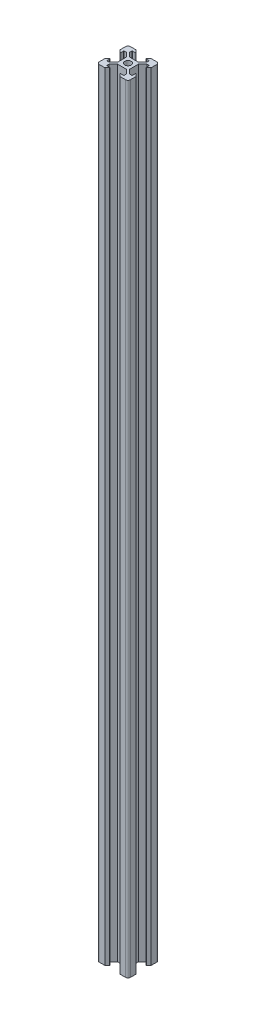
SolidWorks part; units mm, degrees
ref_plane "Alzado" through (0, 0, 0) normal (0, 0, 1) x (1, 0, 0)
ref_plane "Planta" through (0, 0, 0) normal (0, 1, 0) x (1, 0, 0)
ref_plane "Vista lateral" through (0, 0, 0) normal (1, 0, 0) x (0, 0, -1)
sketch "Croquis1" plane through (0, 0, 0) normal (0, 1, 0) x (1, 0, 0)
  line L0 (0, 0) -> (0, 10) construction
  line L1 (-10, 10) -> (10, 10)
  line L2 (-10, 10) -> (-10, -10)
  line L3 (-10, -10) -> (10, -10)
  line L4 (10, 10) -> (10, -10)
  line L5 (-10, 10) -> (10, -10) construction
  line L6 (-10, -10) -> (10, 10) construction
  line L7 (-4.9, 10) -> (-3.1, 8.2)
  line L8 (-3.1, 8.2) -> (-5.5393, 8.2)
  line L9 (-5.5393, 8.2) -> (-5.5393, 6.6)
  line L10 (-5.5393, 6.6) -> (-0.8567, 1.9173)
  line L11 (5.5393, 6.6) -> (0.8567, 1.9173)
  line L12 (5.5393, 8.2) -> (5.5393, 6.6)
  line L13 (3.1, 8.2) -> (5.5393, 8.2)
  line L14 (4.9, 10) -> (3.1, 8.2)
  line L15 (10, 4.9) -> (8.2, 3.1)
  line L16 (8.2, 3.1) -> (8.2, 5.5393)
  line L17 (8.2, 5.5393) -> (6.6, 5.5393)
  line L18 (6.6, 5.5393) -> (1.9173, 0.8567)
  line L19 (6.6, -5.5393) -> (1.9173, -0.8567)
  line L20 (8.2, -5.5393) -> (6.6, -5.5393)
  line L21 (8.2, -3.1) -> (8.2, -5.5393)
  line L22 (10, -4.9) -> (8.2, -3.1)
  line L23 (4.9, -10) -> (3.1, -8.2)
  line L24 (3.1, -8.2) -> (5.5393, -8.2)
  line L25 (5.5393, -8.2) -> (5.5393, -6.6)
  line L26 (5.5393, -6.6) -> (0.8567, -1.9173)
  line L27 (-5.5393, -6.6) -> (-0.8567, -1.9173)
  line L28 (-5.5393, -8.2) -> (-5.5393, -6.6)
  line L29 (-3.1, -8.2) -> (-5.5393, -8.2)
  line L30 (-4.9, -10) -> (-3.1, -8.2)
  line L31 (-10, -4.9) -> (-8.2, -3.1)
  line L32 (-8.2, -3.1) -> (-8.2, -5.5393)
  line L33 (-8.2, -5.5393) -> (-6.6, -5.5393)
  line L34 (-6.6, -5.5393) -> (-1.9173, -0.8567)
  line L35 (-6.6, 5.5393) -> (-1.9173, 0.8567)
  line L36 (-8.2, 5.5393) -> (-6.6, 5.5393)
  line L37 (-8.2, 3.1) -> (-8.2, 5.5393)
  line L38 (-10, 4.9) -> (-8.2, 3.1)
  line L39 (-3.9007, 2.84) -> (-3.9007, -2.84)
  line L40 (2.84, 3.9007) -> (-2.84, 3.9007)
  line L41 (3.9007, -2.84) -> (3.9007, 2.84)
  line L42 (-2.84, -3.9007) -> (2.84, -3.9007)
  circle A0 centre (0, 0) radius 2.1
  point P51 (0, 0)
  point P60 (0, 0)
  dimension "D1" = 4.2
  dimension "D2" = 20
  dimension "D3" = 45
  dimension "D4" = 1.6
  dimension "D5" = 0.75
  dimension "D6" = 1.8
  dimension "D7" = 3.1
  dimension "D9" = 5.68
  dimension "D8" = 4
  dimension "D10" = 4
extrude "Saliente-Extruir1" add sketch "Croquis1" along normal blind 500 contours A0 L10 L9 L8 L7 L1 L2 L38 L37 L36 L35 | A0 L34 L33 L32 L31 L2 L3 L30 L29 L28 L27 | A0 L26 L25 L24 L23 L3 L4 L22 L21 L20 L19 | A0 L18 L17 L16 L15 L4 L1 L14 L13 L12 L11 | A0 L35 L39 L34 | A0 L27 L42 L26 | A0 L19 L41 L18 | A0 L11 L40 L10
fillet "Redondeo1" radius 1.5 4 edges at (10, 250, 10) (-10, 250, 10) (-10, 250, -10) (10, 250, -10)
fillet "Redondeo2" radius 0.2 16 edges at (-5.5393, 250, 8.2) (5.5393, 250, 8.2) (8.2, 250, 5.5393) (8.2, 250, -5.5393) (5.5393, 250, -8.2) (-5.5393, 250, -8.2) (-8.2, 250, -5.5393) (-8.2, 250, 5.5393) (3.1, 250, 8.2) (-3.1, 250, 8.2) (8.2, 250, 3.1) (8.2, 250, -3.1) (3.1, 250, -8.2) (-3.1, 250, -8.2) (-8.2, 250, -3.1) (-8.2, 250, 3.1)
